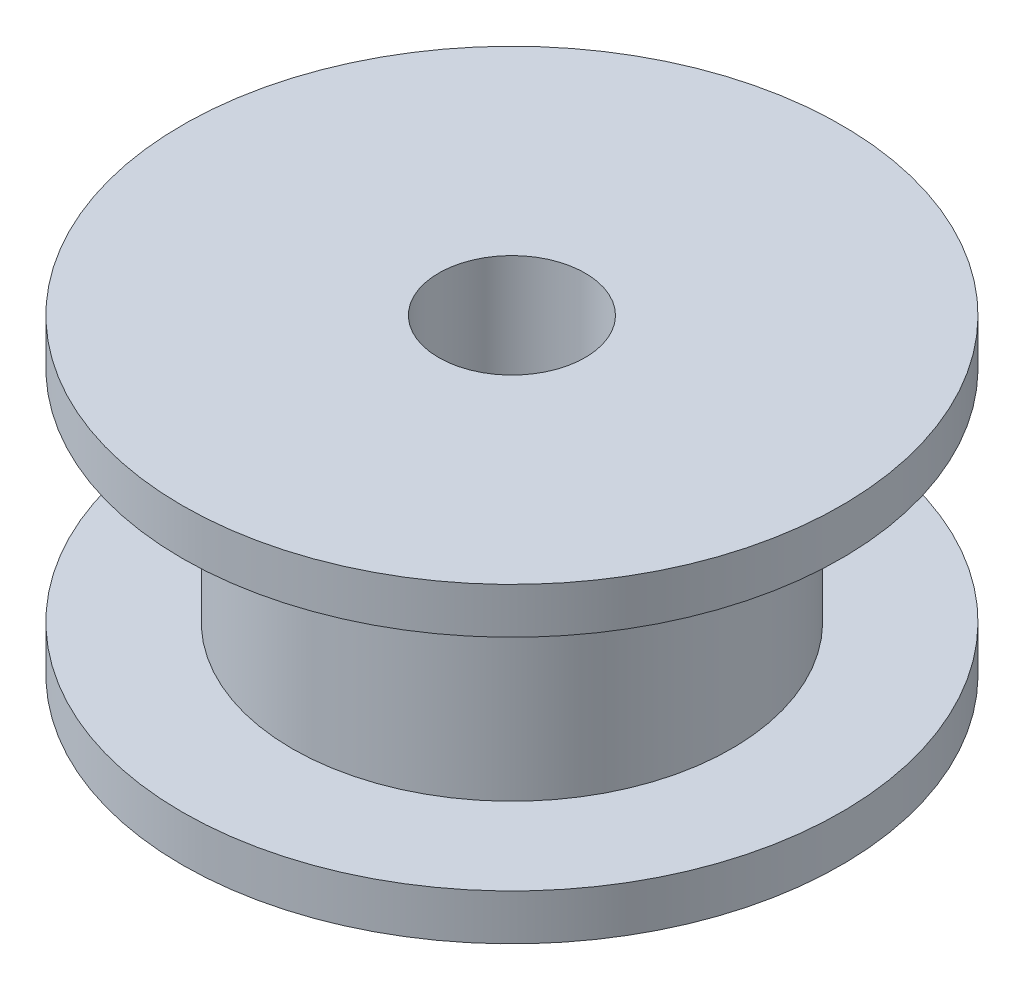
SolidWorks part; units mm, degrees
ref_plane "Front Plane" through (0, 0, 0) normal (0, 0, 1) x (1, 0, 0)
ref_plane "Top Plane" through (0, 0, 0) normal (0, 1, 0) x (1, 0, 0)
ref_plane "Right Plane" through (0, 0, 0) normal (1, 0, 0) x (0, 0, -1)
sketch "Sketch1" plane through (0, 0, 0) normal (0, 1, 0) x (1, 0, 0)
  circle A0 centre (0, 0) radius 9
  dimension "D1" = 18
extrude "Boss-Extrude1" add sketch "Sketch1" along normal blind 1.25
sketch "Sketch2" plane through (0, 1.25, 0) normal (0, 1, 0) x (1, 0, 0)
  line L0 (0, 9) -> (0, -9) construction
  line L2 (-9, 0) -> (9, 0) construction
  circle A0 centre (0, 0) radius 9 construction
  circle A1 centre (0, 0) radius 6
  dimension "D1" = 12
extrude "Boss-Extrude2" add sketch "Sketch2" along normal blind 6
sketch "Sketch3" plane through (0, 7.25, 0) normal (0, 1, 0) x (1, 0, 0)
  circle A0 centre (0, 0) radius 9
  dimension "D1" = 18
extrude "Boss-Extrude3" add sketch "Sketch3" along normal blind 1.25
sketch "Sketch4" plane through (0, 8.5, 0) normal (0, 1, 0) x (1, 0, 0)
  circle A0 centre (0, 0) radius 2
  dimension "D1" = 4
extrude "Cut-Extrude1" cut sketch "Sketch4" against normal blind 10.25
